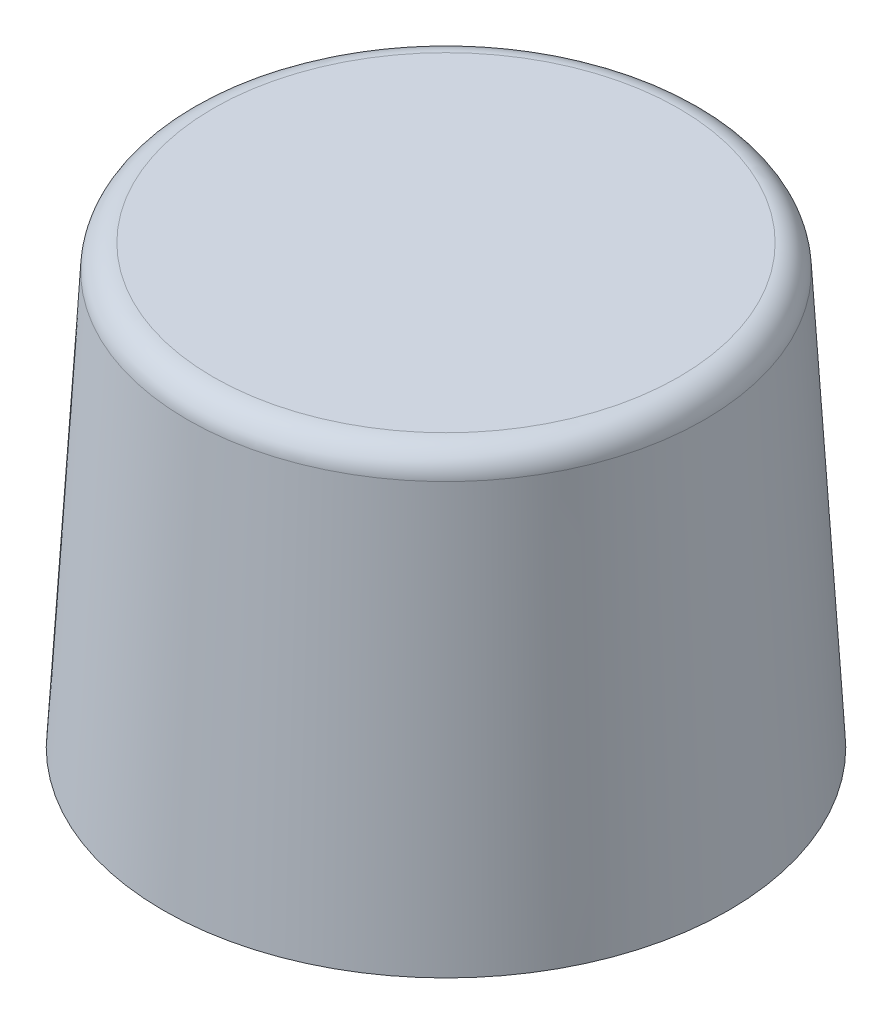
SolidWorks part; units mm, degrees
ref_plane "Piano frontale" through (0, 0, 0) normal (0, 0, 1) x (1, 0, 0)
ref_plane "Piano superiore" through (0, 0, 0) normal (0, 1, 0) x (1, 0, 0)
ref_plane "Piano destro" through (0, 0, 0) normal (1, 0, 0) x (0, 0, -1)
sketch "Schizzo2" plane through (0, 0, 0) normal (0, 0, 1) x (1, 0, 0)
  line L0 (0, 0) -> (11, 0)
  line L2 (11, 0) -> (10, 17)
  line L3 (10, 17) -> (0, 17)
  line L4 (0, 17) -> (0, 0)
  dimension "D1" = 10
  dimension "D2" = 17
  dimension "D3" = 11
revolve "Rivoluzione1" add sketch "Schizzo2" angle 360 about L4
sketch "Schizzo3" plane through (0, 0, 0) normal (0, -1, 0) x (1, 0, 0)
  circle A0 centre (0, 0) radius 3
  dimension "D1" = 6
extrude "Taglio-Estrusione1" cut sketch "Schizzo3" against normal blind 15
fillet "Raccordo1" radius 1 1 edges at (-10, 17, 0)
